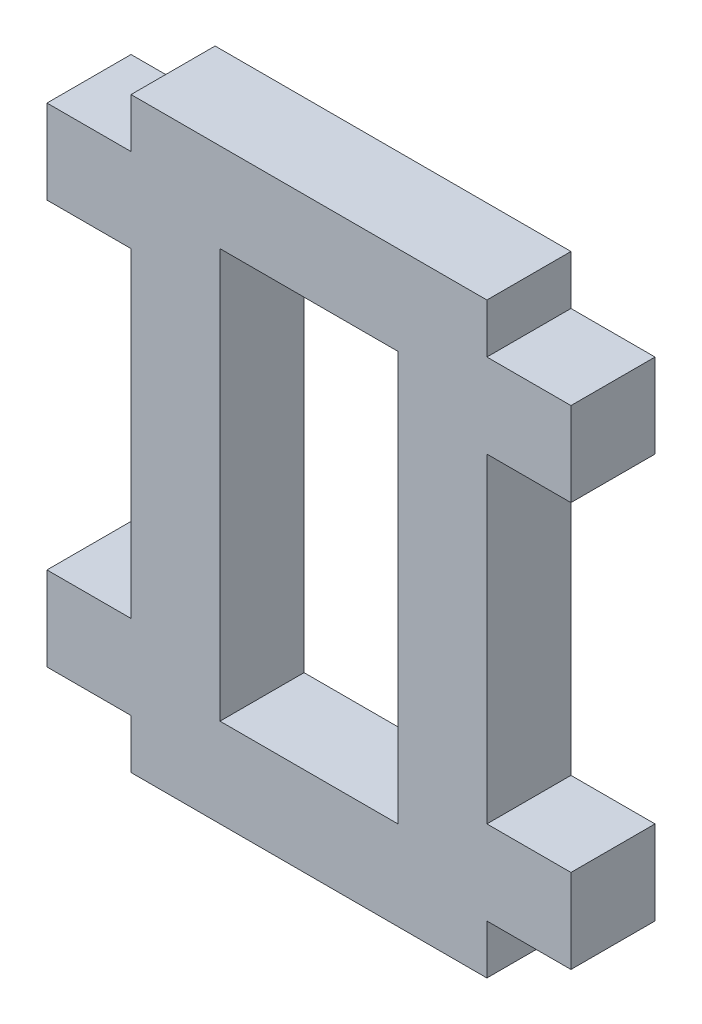
SolidWorks part; units mm, degrees
ref_plane "Front Plane" through (0, 0, 0) normal (0, 0, 1) x (1, 0, 0)
ref_plane "Top Plane" through (0, 0, 0) normal (0, 1, 0) x (1, 0, 0)
ref_plane "Right Plane" through (0, 0, 0) normal (1, 0, 0) x (0, 0, -1)
sketch "Sketch1" plane through (0, 0, 0) normal (0, 0, 1) x (1, 0, 0)
  line L0 (0, 0) -> (-12.7, 0) construction
  line L1 (-12.7, 20.955) -> (12.7, 20.955)
  line L2 (-12.7, 20.955) -> (-12.7, -20.955)
  line L3 (-12.7, -20.955) -> (12.7, -20.955)
  line L4 (12.7, 20.955) -> (12.7, -20.955)
  line L5 (-18.7, 17.43) -> (-12.7, 17.43)
  line L6 (-18.7, 17.43) -> (-18.7, 11.43)
  line L7 (-18.7, 11.43) -> (-12.7, 11.43)
  line L8 (-12.7, 17.43) -> (-12.7, 11.43)
  line L9 (-18.7, 17.43) -> (-12.7, 11.43) construction
  line L10 (-18.7, 11.43) -> (-12.7, 17.43) construction
  line L11 (-18.7, -11.43) -> (-12.7, -11.43)
  line L12 (-18.7, -17.43) -> (-18.7, -11.43)
  line L13 (-18.7, -17.43) -> (-12.7, -17.43)
  line L14 (-12.7, -17.43) -> (-12.7, -11.43)
  line L15 (0, 0) -> (0, 20.955) construction
  line L16 (18.7, 11.43) -> (12.7, 11.43)
  line L17 (12.7, 17.43) -> (12.7, 11.43)
  line L18 (18.7, 17.43) -> (12.7, 17.43)
  line L19 (18.7, 17.43) -> (18.7, 11.43)
  line L20 (18.7, -17.43) -> (18.7, -11.43)
  line L21 (18.7, -17.43) -> (12.7, -17.43)
  line L22 (12.7, -17.43) -> (12.7, -11.43)
  line L23 (18.7, -11.43) -> (12.7, -11.43)
  point P4 (0, 20.955)
  point P6 (-12.7, 0)
  point P7 (-15.7, 14.43)
  point P18 (-15.7, -11.43)
  dimension "D1" = 41.91
  dimension "D2" = 25.4
  dimension "D3" = 6
  dimension "D4" = 22.86
extrude "Boss-Extrude1" add sketch "Sketch1" along normal blind 6 contours L6 L7 L2 L5 | L4 L1 L2 L3 | L12 L13 L2 L11 | L20 L23 L4 L21 | L19 L18 L4 L16
sketch "Sketch2" plane through (0, 0, 6) normal (0, 0, 1) x (1, 0, 0)
  line L49 (-6.35, 14.605) -> (6.35, 14.605)
  line L50 (-12.7, 20.955) -> (12.7, 20.955) construction
  line L51 (-12.7, 20.955) -> (-12.7, -20.955) construction
  line L52 (-12.7, -20.955) -> (12.7, -20.955) construction
  line L53 (12.7, 20.955) -> (12.7, -20.955) construction
  line L54 (6.35, 14.605) -> (6.35, -14.605)
  line L55 (-6.35, -14.605) -> (6.35, -14.605)
  line L56 (-6.35, 14.605) -> (-6.35, -14.605)
  dimension "D1" = 6.35
extrude "Cut-Extrude1" cut sketch "Sketch2" against normal through all
